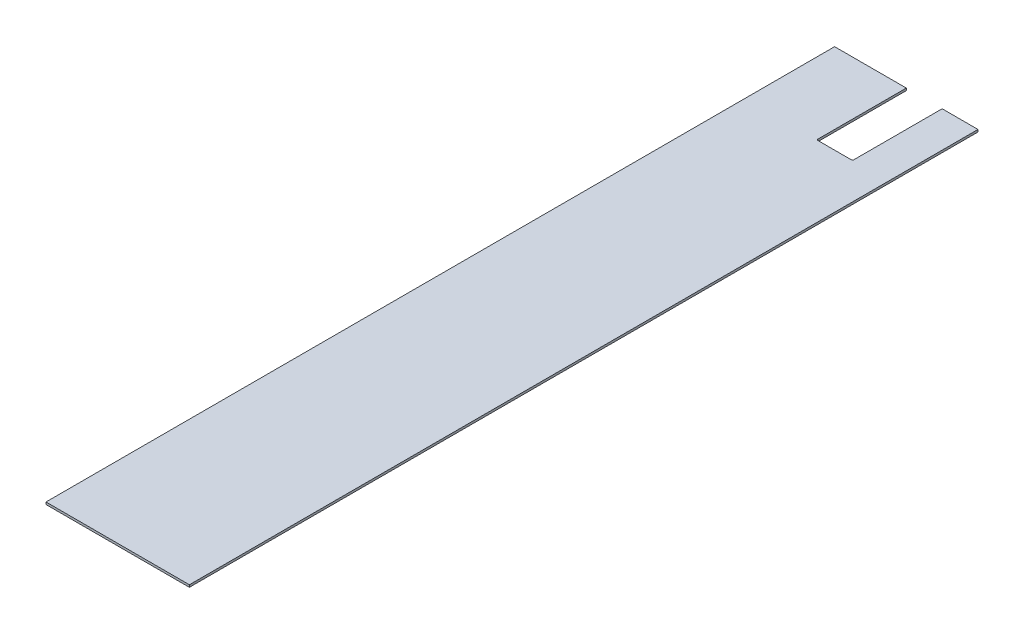
SolidWorks part; units mm, degrees
material "6061 Alloy"
ref_plane "Front Plane" through (0, 0, 0) normal (0, 0, 1) x (1, 0, 0)
ref_plane "Top Plane" through (0, 0, 0) normal (0, 1, 0) x (1, 0, 0)
ref_plane "Right Plane" through (0, 0, 0) normal (1, 0, 0) x (0, 0, -1)
sketch "Sketch1" plane through (0, 0, 0) normal (0, 1, 0) x (1, 0, 0)
  line L0 (0, 1117.6) -> (0, 866.775)
  line L1 (-203.2, 1117.6) -> (0, 1117.6)
  line L2 (-203.2, 1117.6) -> (-203.2, -1117.6)
  line L3 (-203.2, -1117.6) -> (203.2, -1117.6)
  line L4 (203.2, 1117.6) -> (203.2, -1117.6)
  line L5 (-203.2, 1117.6) -> (203.2, -1117.6) construction
  line L6 (-203.2, -1117.6) -> (203.2, 1117.6) construction
  line L7 (3.175, 863.6) -> (98.425, 863.6)
  line L8 (101.6, 866.775) -> (101.6, 1117.6)
  line L9 (101.6, 1117.6) -> (203.2, 1117.6)
  arc A0 (0, 866.775) -> (3.175, 863.6) centre (3.175, 866.775) ccw
  arc A1 (98.425, 863.6) -> (101.6, 866.775) centre (98.425, 866.775) ccw
  point P0 (0, 0)
  dimension "D5" = 3.175
  dimension "D1" = 2235.2
  dimension "D2" = 406.4
  dimension "D3" = 254
  dimension "D4" = 101.6
  dimension "D6" = 101.6
extrude "Boss-Extrude1" add sketch "Sketch1" along normal blind 6.35
